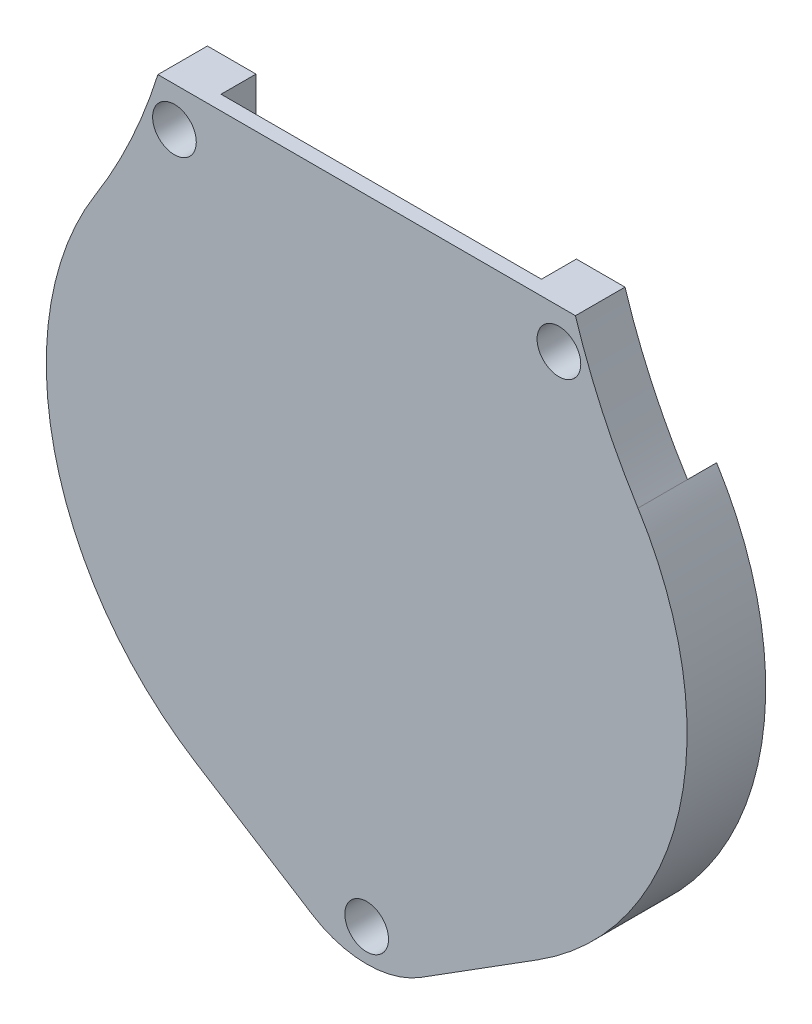
SolidWorks part; units mm, degrees
ref_plane "Front Plane" through (0, 0, 0) normal (0, 0, 1) x (1, 0, 0)
ref_plane "Top Plane" through (0, 0, 0) normal (0, 1, 0) x (1, 0, 0)
ref_plane "Right Plane" through (0, 0, 0) normal (1, 0, 0) x (0, 0, -1)
sketch "Sketch1" plane through (0, 0, 0) normal (0, 0, 1) x (1, 0, 0)
  line L0 (0, 0) -> (0, 110.5744) construction
  line L1 (-15.875, 107.638) -> (-15.875, 41.8859) construction
  line L2 (15.875, 105.2522) -> (15.875, 41.8859) construction
  line L3 (-33.1911, -33.02) -> (48.9076, -33.02) construction
  line L4 (0, 0) -> (0, -55.6039) construction
  line L5 (-4.7378, -30.0359) -> (-14.8903, -23.6415)
  line L6 (4.7378, -30.0359) -> (14.8903, -23.6415)
  line L7 (-46.7853, 13.97) -> (63.7962, 13.97) construction
  line L8 (-37.5439, 26.67) -> (33.7617, 26.67) construction
  line L15 (-18.2073, 26.67) -> (18.2073, 26.67)
  arc A0 (-23.6589, 14.8628) -> (-14.8903, -23.6415) centre (0, 0) ccw
  arc A1 (4.7378, -30.0359) -> (-4.7378, -30.0359) centre (0, -22.5136) cw
  arc A2 (-18.2073, 26.67) -> (-23.6589, 14.8628) centre (-66.675, 41.8859) cw
  arc A3 (18.2073, 26.67) -> (23.6589, 14.8628) centre (66.675, 41.8859) ccw
  arc A4 (23.6589, 14.8628) -> (14.8903, -23.6415) centre (0, 0) cw
  point P15 (0, -33.02)
  dimension "D1" = 31.75
  dimension "D3" = 55.88
  dimension "D5" = 8.89
  dimension "D8" = 50.8
  dimension "D4" = 33.02
  dimension "D6" = 13.97
  dimension "D7" = 12.7
extrude "Boss-Extrude1" add sketch "Sketch1" along normal blind 6.858
sketch "Sketch2" plane through (0, 0, 0) normal (0, 0, -1) x (-1, 0, 0)
  line L0 (-11.7336, 23.241) -> (11.7336, 23.241)
  line L1 (-18.2073, 26.67) -> (18.2073, 26.67) construction
  arc A0 (-11.7336, 23.241) -> (11.7336, 23.241) centre (0, 0) ccw
  dimension "D1" = 3.429
extrude "Cut-Extrude1" cut sketch "Sketch2" against normal blind 6.35
sketch "Sketch3" plane through (0, 0, 0) normal (0, 0, -1) x (-1, 0, 0)
  line L0 (0, 0) -> (0, 57.7751) construction
  line L2 (-13.97, 37.2037) -> (13.97, 37.2037)
  line L3 (-13.97, 37.2037) -> (-13.97, 11.3578)
  line L4 (-13.97, 11.3578) -> (13.97, 11.3578)
  line L5 (13.97, 37.2037) -> (13.97, 11.3578)
  dimension "D1" = 13.97
  dimension "D2" = 27.94
extrude "Cut-Extrude2" cut sketch "Sketch3" against normal blind 5.588
sketch "Sketch4" plane through (0, 0, 6.858) normal (0, 0, 1) x (1, 0, 0)
  circle A0 centre (0, -28.575) radius 1.905
  circle A1 centre (-16.764, 23.241) radius 1.905
  circle A2 centre (16.764, 23.241) radius 1.905
  point P2 (0, 0)
  dimension "D1" = 28.575
  dimension "D2" = 23.241
  dimension "D3" = 23.241
  dimension "D4" = 16.764
  dimension "D5" = 16.764
extrude "Cut-Extrude3" cut sketch "Sketch4" against normal blind 3.175
sketch "Sketch5" plane through (0, 0, 3.683) normal (0, 0, 1) x (1, 0, 0)
  circle A0 centre (-16.764, 23.241) radius 1.143
  circle A1 centre (16.764, 23.241) radius 1.143
  circle A2 centre (0, -28.575) radius 1.143
extrude "Cut-Extrude4" cut sketch "Sketch5" against normal blind 21.59
sketch "Sketch6" plane through (0, 0, 0) normal (0, 0, -1) x (-1, 0, 0)
  line L0 (-18.354, -33.02) -> (21.767, -33.02) construction
  line L1 (0, 0) -> (0, -48.2332) construction
  line L2 (-4.7378, -30.0359) -> (-14.8903, -23.6415) construction
  line L3 (4.7378, -30.0359) -> (14.8903, -23.6415) construction
  line L4 (-15.875, 76.6342) -> (-15.875, 41.8859) construction
  line L5 (15.875, 75.3139) -> (15.875, 41.8859) construction
  line L6 (-23.6589, 14.8628) -> (-4.7378, -30.0359)
  line L7 (23.6589, 14.8628) -> (4.7378, -30.0359)
  line L8 (-18.2073, 26.67) -> (18.2073, 26.67)
  arc A0 (-23.6589, 14.8628) -> (-14.8903, -23.6415) centre (0, 0) ccw construction
  arc A1 (-18.2073, 26.67) -> (-23.6589, 14.8628) centre (-66.675, 41.8859) cw
  arc A2 (23.6589, 14.8628) -> (14.8903, -23.6415) centre (0, 0) cw construction
  arc A3 (18.2073, 26.67) -> (23.6589, 14.8628) centre (66.675, 41.8859) ccw
  arc A4 (4.7378, -30.0359) -> (-4.7378, -30.0359) centre (0, -22.5136) cw
  point P19 (0, -33.02)
  dimension "D2" = 55.88
  dimension "D5" = 50.8
  dimension "D6" = 8.89
  dimension "D1" = 33.02
  dimension "D3" = 31.75
  dimension "D4" = 15.875
extrude "Cut-Extrude5" cut sketch "Sketch6" against normal blind 2.54
